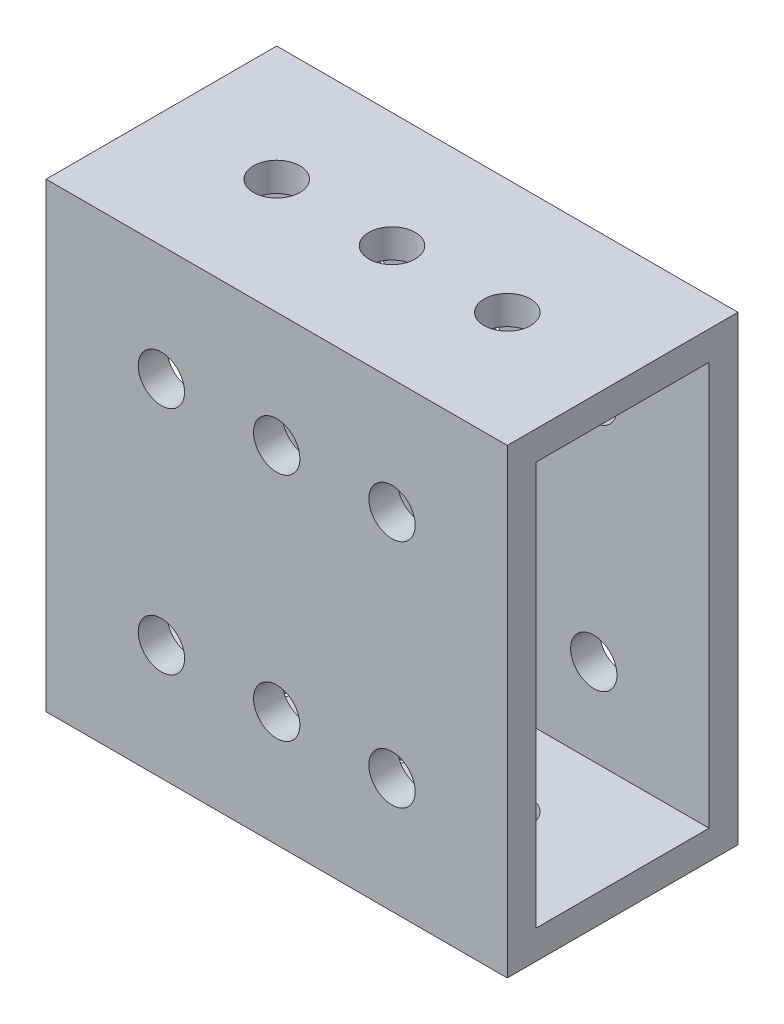
SolidWorks part; units mm, degrees
material "6061-T6 (SS)"
ref_plane "Front Plane" through (0, 0, 0) normal (0, 0, 1) x (1, 0, 0)
ref_plane "Top Plane" through (0, 0, 0) normal (0, 1, 0) x (1, 0, 0)
ref_plane "Right Plane" through (0, 0, 0) normal (1, 0, 0) x (0, 0, -1)
sketch "Sketch1" plane through (0, 0, 0) normal (0, 0, 1) x (1, 0, 0)
  line L1 (0, 0) -> (50.8, 0)
  line L2 (0, 0) -> (0, 50.8)
  line L3 (0, 50.8) -> (50.8, 50.8)
  line L4 (50.8, 0) -> (50.8, 50.8)
  dimension "D1" = 50.8
  dimension "D2" = 50.8
extrude "Boss-Extrude1" add sketch "Sketch1" along normal blind 25.4
sketch "Sketch2" plane through (50.8, 0, 0) normal (1, 0, 0) x (0, 0, -1)
  line L0 (-25.4, 0) -> (0, 0) construction
  line L1 (0, 0) -> (0, 50.8) construction
  line L2 (-25.4, 50.8) -> (0, 50.8) construction
  line L3 (-22.225, 3.175) -> (-3.175, 3.175)
  line L4 (-22.225, 3.175) -> (-22.225, 47.625)
  line L5 (-22.225, 47.625) -> (-3.175, 47.625)
  line L6 (-3.175, 3.175) -> (-3.175, 47.625)
  line L8 (-25.4, 0) -> (-25.4, 50.8) construction
  dimension "D1" = 3.175
  dimension "D2" = 3.175
  dimension "D3" = 3.175
  dimension "D4" = 3.175
extrude "Cut-Extrude1" cut sketch "Sketch2" against normal through all
sketch "Sketch3" plane through (0, 50.8, 0) normal (0, 1, 0) x (1, 0, 0)
  line L0 (50.8, 0) -> (0, 0) construction
  line L1 (0, -25.4) -> (0, 0) construction
  line L2 (50.8, -25.4) -> (0, -25.4) construction
  circle A0 centre (12.7, -12.7) radius 2.5527
  circle A1 centre (25.4, -12.7) radius 2.5527
  circle A2 centre (38.1, -12.7) radius 2.5527
  dimension "D1" = 12.7
  dimension "D2" = 12.7
  dimension "D3" = 12.7
  dimension "D4" = 12.7
  dimension "D5" = 5.1054
  dimension "D6" = 12.7
  dimension "D7" = 12.7
sketch "Sketch4" plane through (0, 0, 0) normal (0, 0, -1) x (-1, 0, 0)
  line L0 (-50.8, 0) -> (-50.8, 50.8) construction
  line L1 (-50.8, 50.8) -> (0, 50.8) construction
  line L2 (-22.8473, 50.8) -> (-27.9527, 50.8) construction
  line L4 (0, 50.8) -> (0, 0) construction
  circle A0 centre (-38.1, 38.1) radius 2.5527
  circle A1 centre (-25.4, 38.1) radius 2.5527
  circle A2 centre (-12.7, 38.1) radius 2.5527
  circle A3 centre (-38.1, 12.7) radius 2.5527
  circle A4 centre (-25.4, 12.7) radius 2.5527
  circle A5 centre (-12.7, 12.7) radius 2.5527
  dimension "D1" = 12.7
  dimension "D2" = 12.7
  dimension "D3" = 12.7
  dimension "D4" = 5.1054
  dimension "D5" = 12.7
  dimension "D6" = 12.7
  dimension "D7" = 12.7
  dimension "D8" = 5.1054
  dimension "D9" = 12.7
  dimension "D10" = 25.4
  dimension "D11" = 3
  dimension "D12" = 12.7
extrude "Cut-Extrude2" cut sketch "Sketch3" against normal through all
extrude "Cut-Extrude3" cut sketch "Sketch4" against normal through all
